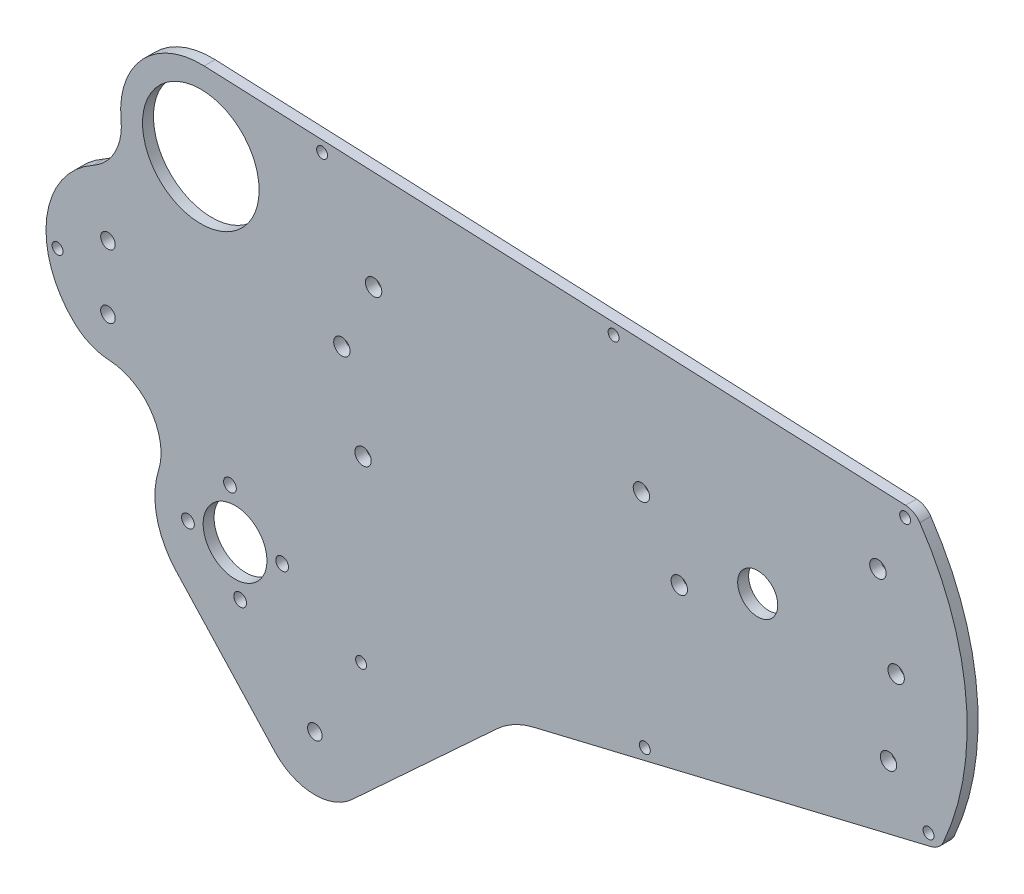
SolidWorks part; units mm, degrees
ref_plane "Front Plane" through (0, 0, 0) normal (0, 0, 1) x (1, 0, 0)
ref_plane "Top Plane" through (0, 0, 0) normal (0, 1, 0) x (1, 0, 0)
ref_plane "Right Plane" through (0, 0, 0) normal (1, 0, 0) x (0, 0, -1)
sketch "Sketch1" plane through (0, 0, 0) normal (0, 0, 1) x (1, 0, 0)
  line L0 (86.8854, -33.5) -> (-137.2004, -33.5) construction
  line L1 (-111.886, 49.4802) -> (80.595, 41.3179)
  line L2 (-115.2069, 49.6211) -> (-101.035, -81.6153) construction
  line L3 (-97.8208, -80.7688) -> (92.1699, -30.731) construction
  line L4 (78.7977, 41.3942) -> (86.7407, -32.1609) construction
  line L5 (-108.121, -15.9971) -> (82.7692, 4.6166) construction
  line L6 (91, -33.5) -> (-88.5, -33.5) construction
  line L7 (-97.4673, 5.5) -> (-155.3054, 5.5) construction
  line L8 (-138.3, -14) -> (-155.3054, -14) construction
  line L9 (-138.3, 5.5) -> (-138.3, -33.5) construction
  line L10 (-155.3054, 5.5) -> (-155.3054, -33.5) construction
  line L11 (40.0178, 33.5) -> (40.0178, -33.5) construction
  line L12 (-101.0425, -81.5467) -> (-90.8208, -79.0963)
  line L13 (-91.5, 33.5) -> (88, 33.5) construction
  line L14 (-68.3, -21.5) -> (-107.0746, -25.6872) construction
  line L15 (-138.3, -5.25) -> (-81.5148, -93.5701) construction
  line L17 (-119.5948, -74.4106) -> (-92.5405, -103.7404)
  line L18 (-71.3446, -104.5958) -> (-31.4414, -67.7885)
  line L19 (-21.4819, -62.4739) -> (87.5999, -36.3241)
  circle A0 centre (40.0178, 0) radius 5.5
  circle A1 centre (-112.8181, 27.5) radius 13 construction
  circle A2 centre (-103.4238, -59.4942) radius 13 construction
  arc A3 (-91.5, 33.5) -> (-88.5, -33.5) centre (-18.0922, 3.2198) ccw construction
  circle A4 centre (-68.3, -21.5) radius 2.25
  circle A6 centre (-138.3, -5.25) radius 2
  circle A7 centre (-138.3, -22.75) radius 2
  arc A8 (-142.3827, 10.6321) -> (-147.5429, -29.3643) centre (-130.3054, -11.2571) ccw
  arc A9 (-147.5429, -29.3643) -> (-137.2004, -33.5) centre (-137.2004, -18.5) ccw
  circle A10 centre (-112.8181, 27.5) radius 22
  arc A11 (87.5999, -36.3241) -> (91, -33.5) centre (86.4343, -31.4619) ccw
  circle A12 centre (-103.4238, -59.4942) radius 22
  arc A13 (91, -33.5) -> (84.5157, 39.1371) centre (22.6589, -2.9929) ccw
  arc A14 (91, -33.5) -> (88, 33.5) centre (22.6589, -2.9929) ccw construction
  arc A15 (84.5157, 39.1371) -> (80.595, 41.3179) centre (80.3831, 36.3224) ccw
  arc A17 (-124.4228, -52.9336) -> (-137.9704, -33.4802) centre (-138.7403, -48.4604) ccw
  arc A18 (-142.3827, 10.6321) -> (-134.7058, 25.2795) centre (-149.6292, 23.7656) ccw
  circle A19 centre (-74.1, 1.7) radius 2.25
  circle A20 centre (-65.4, 20.2) radius 2.25
  circle A21 centre (8.1, 8.2) radius 2.25
  circle A23 centre (18.5, -8.7) radius 2.25
  circle A25 centre (78, -0.1) radius 2.25
  circle A26 centre (75.9, -21.8) radius 2.25
  circle A27 centre (73, 22.4) radius 2.25
  circle A30 centre (-81.5148, -93.5701) radius 2
  circle A36 centre (-114.2138, 40.4249) radius 1.75
  circle A37 centre (-99.8933, 28.8957) radius 1.75
  circle A38 centre (-111.4224, 14.5751) radius 1.75
  circle A39 centre (-125.743, 26.1043) radius 1.75
  circle A40 centre (-104.8196, -46.5694) radius 1.75
  circle A41 centre (-90.499, -58.0985) radius 1.75
  circle A42 centre (-102.0281, -72.4191) radius 1.75
  circle A43 centre (-116.3487, -60.89) radius 1.75
  circle A44 centre (40.0178, 0) radius 35 construction
  circle A45 centre (40.0178, 0) radius 43
  circle A49 centre (-103.4238, -59.4942) radius 16
  circle A50 centre (-112.8181, 27.5) radius 16
  circle A51 centre (-112.8181, 27.5) radius 8.75
  circle A52 centre (-103.4238, -59.4942) radius 8.75
  arc A53 (91, -33.5) -> (88, 33.5) centre (22.6589, -2.9929) ccw construction
  arc A54 (-92.5405, -103.7404) -> (-71.3446, -104.5958) centre (-81.5148, -93.5701) ccw
  arc A55 (-21.4819, -62.4739) -> (-31.4414, -67.7885) centre (-16.2632, -84.2433) ccw
  circle A56 centre (-68.3, -21.5) radius 2.25 construction
  circle A57 centre (-74.1, 1.7) radius 2.25 construction
  circle A58 centre (-65.4, 20.2) radius 2.25 construction
  circle A59 centre (18.5, -8.7) radius 2.25 construction
  circle A60 centre (8.1, 8.2) radius 2.25 construction
  circle A61 centre (75.9, -21.8) radius 2.25 construction
  circle A62 centre (78, -0.1) radius 2.25 construction
  circle A63 centre (73, 22.4) radius 2.25 construction
  point P52 (82.7692, 4.6166)
  point P109 (-112.8181, 27.5)
  point P118 (-103.4238, -59.4942)
  dimension "D5" = 4
  dimension "D6" = 25
  dimension "D9" = 15
  dimension "D13" = 10
  dimension "D14" = 26
  dimension "D11" = 44
  dimension "D15" = 3.5
  dimension "D12" = 70
  dimension "D19" = 11
  dimension "D20" = 17.5
  dimension "D22" = 32
  dimension "D24" = 4
  dimension "D2" = 39
  dimension "D3" = 70
  dimension "D4" = 17.5
  dimension "D7" = 14
  dimension "D8" = 10
  dimension "D10" = 87.5
  dimension "D21" = 192
  dimension "D23" = 39
  dimension "D25" = 105
  dimension "D18" = 8
  dimension "D16" = 4
  dimension "D17" = 4
extrude "Boss-Extrude1" add sketch "Sketch1" along normal blind 3
sketch "Sketch2" plane through (0, 0, 3) normal (0, 0, 1) x (1, 0, 0)
  line L0 (86.9005, -33.4068) -> (9.0348, -52.0733) construction
  line L1 (-138.3, -5.25) -> (-138.3, -22.75) construction
  line L2 (9.0348, -52.0733) -> (-68.831, -70.7397) construction
  line L9 (-79.5321, 45.1056) -> (0.4679, 41.7131) construction
  line L10 (0.4679, 41.7131) -> (80.4679, 38.3206) construction
  line L12 (80.4679, 38.3206) -> (-112.0131, 46.4829)
  line L13 (-117.3897, -72.3766) -> (-90.3354, -101.7064)
  line L14 (-73.3786, -102.3907) -> (-33.4755, -65.5833)
  line L15 (-22.1813, -59.5566) -> (86.9005, -33.4068)
  line L16 (80.4679, 38.3206) -> (-112.0131, 46.4829) construction
  line L17 (-117.3897, -72.3766) -> (-90.3354, -101.7064) construction
  line L18 (-73.3786, -102.3907) -> (-33.4755, -65.5833) construction
  line L19 (-109.8329, -80.569) -> (86.9005, -33.4068) construction
  circle A0 centre (9.0348, -52.0733) radius 1.5
  circle A2 centre (-68.831, -70.7397) radius 1.5
  arc A14 (82.0361, 37.4483) -> (80.4679, 38.3206) centre (80.3831, 36.3224) ccw
  arc A15 (82.0361, 37.4483) -> (80.4679, 38.3206) centre (80.3831, 36.3224) ccw
  arc A16 (86.9005, -33.4068) -> (88.2606, -32.2771) centre (86.4343, -31.4619) ccw
  arc A17 (-114.6056, -75.3948) -> (-102.9876, -78.928) centre (-105.7851, -67.2586) ccw construction
  circle A21 centre (86.9005, -33.4068) radius 1.5
  circle A23 centre (80.4679, 38.3206) radius 1.5
  circle A24 centre (0.4679, 41.7131) radius 1.5
  circle A27 centre (-79.5321, 45.1056) radius 1.5
  arc A28 (-112.0131, 46.4829) -> (-131.7211, 25.5823) centre (-112.8181, 27.5) ccw
  arc A29 (-140.9335, 8.0053) -> (-131.7211, 25.5823) centre (-149.6292, 23.7656) ccw
  arc A30 (-140.9335, 8.0053) -> (-145.4744, -27.1914) centre (-130.3054, -11.2571) ccw
  arc A31 (-145.4744, -27.1914) -> (-137.8164, -30.4842) centre (-137.2004, -18.5) ccw
  arc A32 (-121.5593, -53.8282) -> (-137.8164, -30.4842) centre (-138.7403, -48.4604) ccw
  arc A33 (-121.5593, -53.8282) -> (-117.3897, -72.3766) centre (-103.4238, -59.4942) ccw
  arc A34 (-90.3354, -101.7064) -> (-73.3786, -102.3907) centre (-81.5148, -93.5701) ccw
  arc A35 (-22.1813, -59.5566) -> (-33.4755, -65.5833) centre (-16.2632, -84.2433) ccw
  arc A36 (88.2606, -32.2771) -> (82.0361, 37.4483) centre (22.6589, -2.9929) ccw
  arc A37 (-112.0131, 46.4829) -> (-131.7211, 25.5823) centre (-112.8181, 27.5) ccw construction
  arc A38 (-140.9335, 8.0053) -> (-131.7211, 25.5823) centre (-149.6292, 23.7656) ccw construction
  arc A39 (-140.9335, 8.0053) -> (-145.4744, -27.1914) centre (-130.3054, -11.2571) ccw construction
  arc A40 (-145.4744, -27.1914) -> (-137.8164, -30.4842) centre (-137.2004, -18.5) ccw construction
  arc A41 (-121.5593, -53.8282) -> (-137.8164, -30.4842) centre (-138.7403, -48.4604) ccw construction
  arc A42 (-121.5593, -53.8282) -> (-117.3897, -72.3766) centre (-103.4238, -59.4942) ccw construction
  arc A43 (-90.3354, -101.7064) -> (-73.3786, -102.3907) centre (-81.5148, -93.5701) ccw construction
  arc A44 (-22.1813, -59.5566) -> (-33.4755, -65.5833) centre (-16.2632, -84.2433) ccw construction
  arc A45 (88.2606, -32.2771) -> (82.0361, 37.4483) centre (22.6589, -2.9929) ccw construction
  circle A47 centre (-152.1337, -14) radius 1.5
  arc A51 (86.9005, -33.4068) -> (88.2606, -32.2771) centre (86.4343, -31.4619) ccw
  point P2 (-138.3, -14)
  dimension "D4" = 3
  dimension "D2" = 80
  dimension "D1" = 3
extrude "Cut-Extrude1" cut sketch "Sketch2" against normal through all
